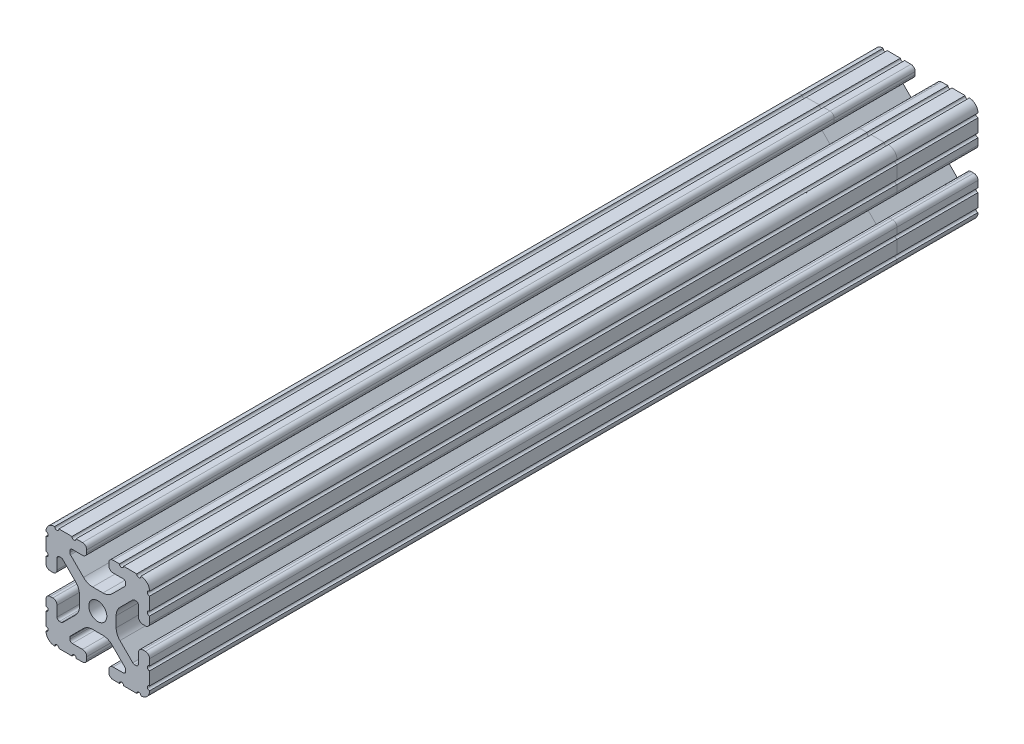
SolidWorks part; units mm, degrees
ref_plane "Front Plane" through (0, 0, 0) normal (0, 0, 1) x (1, 0, 0)
ref_plane "Top Plane" through (0, 0, 0) normal (0, 1, 0) x (1, 0, 0)
ref_plane "Right Plane" through (0, 0, 0) normal (1, 0, 0) x (0, 0, -1)
ref_plane "Plane1" through (0, 0, -304.8) normal (0, 0, -1) x (-1, 0, 0)
sketch "Sketch1" plane through (0, 0, -304.8) normal (0, 0, -1) x (-1, 0, 0)
  line L0 (14.3277, 19.05) -> (9.4982, 19.05)
  line L1 (7.9742, 19.05) -> (5.6176, 19.05)
  line L2 (4.064, 17.4964) -> (4.064, 16.5396)
  line L3 (5.6176, 14.986) -> (9.3853, 14.986)
  line L4 (10.287, 14.0843) -> (10.287, 13.5524)
  line L5 (10.0229, 12.9148) -> (5.2522, 8.144)
  line L6 (1.9022, 6.7564) -> (-1.9022, 6.7564)
  line L7 (-5.2522, 8.144) -> (-10.0229, 12.9148)
  line L8 (-10.287, 13.5524) -> (-10.287, 14.0843)
  line L9 (-9.3853, 14.986) -> (-5.6176, 14.986)
  line L10 (-4.064, 16.5396) -> (-4.064, 17.4964)
  line L11 (-5.6176, 19.05) -> (-7.9742, 19.05)
  line L12 (-9.4982, 19.05) -> (-14.3277, 19.05)
  line L13 (-19.05, 14.3277) -> (-19.05, 9.4961)
  line L14 (-19.05, 7.9763) -> (-19.05, 5.6176)
  line L15 (-17.4964, 4.064) -> (-16.5396, 4.064)
  line L16 (-14.986, 5.6176) -> (-14.986, 9.3853)
  line L17 (-14.0843, 10.287) -> (-13.516, 10.287)
  line L18 (-12.8784, 10.0229) -> (-8.1476, 5.2921)
  line L19 (-6.7564, 1.9335) -> (-6.7564, -1.9335)
  line L20 (-8.1476, -5.2921) -> (-12.8784, -10.0229)
  line L21 (-13.516, -10.287) -> (-14.0843, -10.287)
  line L22 (-14.986, -9.3853) -> (-14.986, -5.6176)
  line L23 (-16.5396, -4.064) -> (-17.4964, -4.064)
  line L24 (-19.05, -5.6176) -> (-19.05, -7.9763)
  line L25 (-19.05, -9.4961) -> (-19.05, -14.3277)
  line L26 (-14.3277, -19.05) -> (-9.4961, -19.05)
  line L27 (-7.9763, -19.05) -> (-5.6176, -19.05)
  line L28 (-4.064, -17.4964) -> (-4.064, -16.5396)
  line L29 (-5.6176, -14.986) -> (-9.3853, -14.986)
  line L30 (-10.287, -14.0843) -> (-10.287, -13.5524)
  line L31 (-10.0229, -12.9148) -> (-5.2522, -8.144)
  line L32 (-1.9022, -6.7564) -> (1.9022, -6.7564)
  line L33 (5.2522, -8.144) -> (10.0229, -12.9148)
  line L34 (10.287, -13.5524) -> (10.287, -14.0843)
  line L35 (9.3853, -14.986) -> (5.6176, -14.986)
  line L36 (4.064, -16.5396) -> (4.064, -17.4964)
  line L37 (5.6176, -19.05) -> (7.9763, -19.05)
  line L38 (9.4961, -19.05) -> (14.3277, -19.05)
  line L39 (19.05, -14.3277) -> (19.05, -9.4961)
  line L40 (19.05, -7.9763) -> (19.05, -5.6176)
  line L41 (17.4964, -4.064) -> (16.5396, -4.064)
  line L42 (14.986, -5.6176) -> (14.986, -9.3853)
  line L43 (14.0843, -10.287) -> (13.516, -10.287)
  line L44 (12.8784, -10.0229) -> (8.1476, -5.2921)
  line L45 (6.7564, -1.9335) -> (6.7564, 1.9335)
  line L46 (8.1476, 5.2921) -> (12.8784, 10.0229)
  line L47 (13.516, 10.287) -> (14.0843, 10.287)
  line L48 (14.986, 9.3853) -> (14.986, 5.6176)
  line L49 (16.5396, 4.064) -> (17.4964, 4.064)
  line L50 (19.05, 5.6176) -> (19.05, 7.9763)
  line L51 (19.05, 9.4961) -> (19.05, 14.3277)
  line L52 (19.05, 5.6176) -> (17.4964, 5.6176) construction
  line L53 (17.4964, 5.6176) -> (17.4964, 4.064) construction
  line L54 (17.4964, 5.6176) -> (18.5393, 4.466) construction
  arc A0 (15.8475, 19.05) -> (14.3277, 19.05) centre (15.0876, 18.9933) cw
  arc A1 (9.4982, 19.05) -> (7.9742, 19.05) centre (8.7362, 19.05) cw
  arc A2 (5.6176, 19.05) -> (4.064, 17.4964) centre (5.6176, 17.4964) ccw
  arc A3 (4.064, 16.5396) -> (5.6176, 14.986) centre (5.6176, 16.5396) ccw
  arc A4 (9.3853, 14.986) -> (10.287, 14.0843) centre (9.3853, 14.0843) cw
  arc A5 (10.287, 13.5524) -> (10.0229, 12.9148) centre (9.3853, 13.5524) cw
  arc A6 (5.2522, 8.144) -> (1.9022, 6.7564) centre (1.9022, 11.494) cw
  arc A7 (-1.9022, 6.7564) -> (-5.2522, 8.144) centre (-1.9022, 11.494) cw
  arc A8 (-10.0229, 12.9148) -> (-10.287, 13.5524) centre (-9.3853, 13.5524) cw
  arc A9 (-10.287, 14.0843) -> (-9.3853, 14.986) centre (-9.3853, 14.0843) cw
  arc A10 (-5.6176, 14.986) -> (-4.064, 16.5396) centre (-5.6176, 16.5396) ccw
  arc A11 (-4.064, 17.4964) -> (-5.6176, 19.05) centre (-5.6176, 17.4964) ccw
  arc A12 (-7.9742, 19.05) -> (-9.4982, 19.05) centre (-8.7362, 19.05) cw
  arc A13 (-14.3277, 19.05) -> (-15.8475, 19.05) centre (-15.0876, 18.9933) cw
  arc A14 (-15.8475, 19.05) -> (-19.05, 15.8475) centre (-15.8751, 15.8751) ccw
  arc A15 (-19.05, 15.8475) -> (-19.05, 14.3277) centre (-18.9933, 15.0876) cw
  arc A16 (-19.05, 9.4961) -> (-19.05, 7.9763) centre (-18.9933, 8.7362) cw
  arc A17 (-19.05, 5.6176) -> (-17.4964, 4.064) centre (-17.4964, 5.6176) ccw
  arc A18 (-16.5396, 4.064) -> (-14.986, 5.6176) centre (-16.5396, 5.6176) ccw
  arc A19 (-14.986, 9.3853) -> (-14.0843, 10.287) centre (-14.0843, 9.3853) cw
  arc A20 (-13.516, 10.287) -> (-12.8784, 10.0229) centre (-13.516, 9.3853) cw
  arc A21 (-8.1476, 5.2921) -> (-6.7564, 1.9335) centre (-11.5062, 1.9335) cw
  arc A22 (-6.7564, -1.9335) -> (-8.1476, -5.2921) centre (-11.5062, -1.9335) cw
  arc A23 (-12.8784, -10.0229) -> (-13.516, -10.287) centre (-13.516, -9.3853) cw
  arc A24 (-14.0843, -10.287) -> (-14.986, -9.3853) centre (-14.0843, -9.3853) cw
  arc A25 (-14.986, -5.6176) -> (-16.5396, -4.064) centre (-16.5396, -5.6176) ccw
  arc A26 (-17.4964, -4.064) -> (-19.05, -5.6176) centre (-17.4964, -5.6176) ccw
  arc A27 (-19.05, -7.9763) -> (-19.05, -9.4961) centre (-18.9933, -8.7362) cw
  arc A28 (-19.05, -14.3277) -> (-19.05, -15.8475) centre (-18.9933, -15.0876) cw
  arc A29 (-19.05, -15.8475) -> (-15.8475, -19.05) centre (-15.8751, -15.8751) ccw
  arc A30 (-15.8475, -19.05) -> (-14.3277, -19.05) centre (-15.0876, -18.9933) cw
  arc A31 (-9.4961, -19.05) -> (-7.9763, -19.05) centre (-8.7362, -18.9933) cw
  arc A32 (-5.6176, -19.05) -> (-4.064, -17.4964) centre (-5.6176, -17.4964) ccw
  arc A33 (-4.064, -16.5396) -> (-5.6176, -14.986) centre (-5.6176, -16.5396) ccw
  arc A34 (-9.3853, -14.986) -> (-10.287, -14.0843) centre (-9.3853, -14.0843) cw
  arc A35 (-10.287, -13.5524) -> (-10.0229, -12.9148) centre (-9.3853, -13.5524) cw
  arc A36 (-5.2522, -8.144) -> (-1.9022, -6.7564) centre (-1.9022, -11.494) cw
  arc A37 (1.9022, -6.7564) -> (5.2522, -8.144) centre (1.9022, -11.494) cw
  arc A38 (10.0229, -12.9148) -> (10.287, -13.5524) centre (9.3853, -13.5524) cw
  arc A39 (10.287, -14.0843) -> (9.3853, -14.986) centre (9.3853, -14.0843) cw
  arc A40 (5.6176, -14.986) -> (4.064, -16.5396) centre (5.6176, -16.5396) ccw
  arc A41 (4.064, -17.4964) -> (5.6176, -19.05) centre (5.6176, -17.4964) ccw
  arc A42 (7.9763, -19.05) -> (9.4961, -19.05) centre (8.7362, -18.9933) cw
  arc A43 (14.3277, -19.05) -> (15.8475, -19.05) centre (15.0876, -18.9933) cw
  arc A44 (15.8475, -19.05) -> (19.05, -15.8475) centre (15.8751, -15.8751) ccw
  arc A45 (19.05, -15.8475) -> (19.05, -14.3277) centre (18.9933, -15.0876) cw
  arc A46 (19.05, -9.4961) -> (19.05, -7.9763) centre (18.9933, -8.7362) cw
  arc A47 (19.05, -5.6176) -> (17.4964, -4.064) centre (17.4964, -5.6176) ccw
  arc A48 (16.5396, -4.064) -> (14.986, -5.6176) centre (16.5396, -5.6176) ccw
  arc A49 (14.986, -9.3853) -> (14.0843, -10.287) centre (14.0843, -9.3853) cw
  arc A50 (13.516, -10.287) -> (12.8784, -10.0229) centre (13.516, -9.3853) cw
  arc A51 (8.1476, -5.2921) -> (6.7564, -1.9335) centre (11.5062, -1.9335) cw
  arc A52 (6.7564, 1.9335) -> (8.1476, 5.2921) centre (11.5062, 1.9335) cw
  arc A53 (12.8784, 10.0229) -> (13.516, 10.287) centre (13.516, 9.3853) cw
  arc A54 (14.0843, 10.287) -> (14.986, 9.3853) centre (14.0843, 9.3853) cw
  arc A55 (14.986, 5.6176) -> (16.5396, 4.064) centre (16.5396, 5.6176) ccw
  arc A56 (17.4964, 4.064) -> (19.05, 5.6176) centre (17.4964, 5.6176) ccw
  arc A57 (19.05, 7.9763) -> (19.05, 9.4961) centre (18.9933, 8.7362) cw
  arc A58 (19.05, 14.3277) -> (19.05, 15.8475) centre (18.9933, 15.0876) cw
  arc A59 (19.05, 15.8475) -> (15.8475, 19.05) centre (15.8751, 15.8751) ccw
  circle A60 centre (0, 0) radius 3.3274
sketch "Sketch2" plane through (0, 0, 0) normal (0, 1, 0) x (1, 0, 0)
  line L1 (0, 275) -> (0, 304.8)
  line L2 (0, 275) -> (0, 0)
sweep "Sweep4" add profiles "Sketch1" path "Sketch2"
